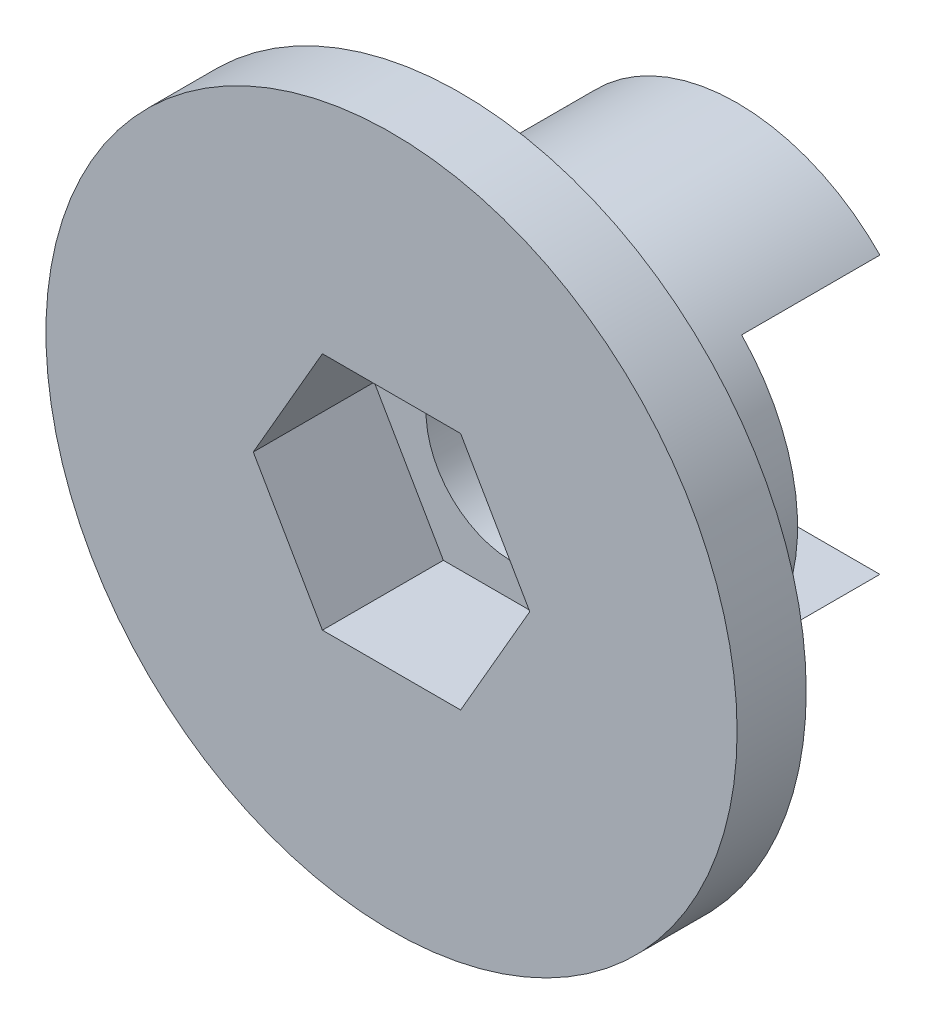
SolidWorks part; units mm, degrees
ref_plane "Front Plane" through (0, 0, 0) normal (0, 0, 1) x (1, 0, 0)
ref_plane "Top Plane" through (0, 0, 0) normal (0, 1, 0) x (1, 0, 0)
ref_plane "Right Plane" through (0, 0, 0) normal (1, 0, 0) x (0, 0, -1)
sketch "Sketch1" plane through (0, 0, 0) normal (0, 0, 1) x (1, 0, 0)
  circle A0 centre (0, 0) radius 11.5
  circle A1 centre (0, 0) radius 5
  dimension "D1" = 23
  dimension "D2" = 10
extrude "Boss-Extrude1" add sketch "Sketch1" along normal blind 20
sketch "Sketch2" plane through (0, 0, 20) normal (0, 0, 1) x (1, 0, 0)
  line L1 (8, 0) -> (4, 6.9282)
  line L2 (4, 6.9282) -> (-4, 6.9282)
  line L3 (-4, 6.9282) -> (-8, 0)
  line L4 (-8, 0) -> (-4, -6.9282)
  line L5 (-4, -6.9282) -> (4, -6.9282)
  line L6 (4, -6.9282) -> (8, 0)
  circle A0 centre (0, 0) radius 6.9282 construction
  dimension "D1" = 16
extrude "Cut-Extrude1" cut sketch "Sketch2" against normal blind 7
sketch "Sketch3" plane through (0, 0, 0) normal (1, 0, 0) x (0, 0, -1)
  line L0 (0, -11.5) -> (0, 11.5) construction
  line L1 (0, 8) -> (-8, 8)
  line L2 (0, 8) -> (0, -8)
  line L3 (0, -8) -> (-8, -8)
  line L4 (-8, 8) -> (-8, -8)
  point P6 (-8, 0)
  dimension "D1" = 16
  dimension "D2" = 8
extrude "Cut-Extrude2" cut sketch "Sketch3" against normal through all and the other way through all
sketch "Sketch4" plane through (0, 0, 20) normal (0, 0, 1) x (1, 0, 0)
  circle A0 centre (0, 0) radius 11.5 construction
  circle A1 centre (0, 0) radius 11.5
  circle A2 centre (0, 0) radius 20
  dimension "D1" = 40
extrude "Boss-Extrude2" add sketch "Sketch4" against normal blind 4
sketch "Sketch5" plane through (0, 0, 13) normal (0, 0, 1) x (1, 0, 0)
  circle A0 centre (0, 0) radius 5 construction
  circle A1 centre (0, 0) radius 5
extrude "Boss-Extrude3" [suppressed] add sketch "Sketch5" along normal blind 0.2 separate body
